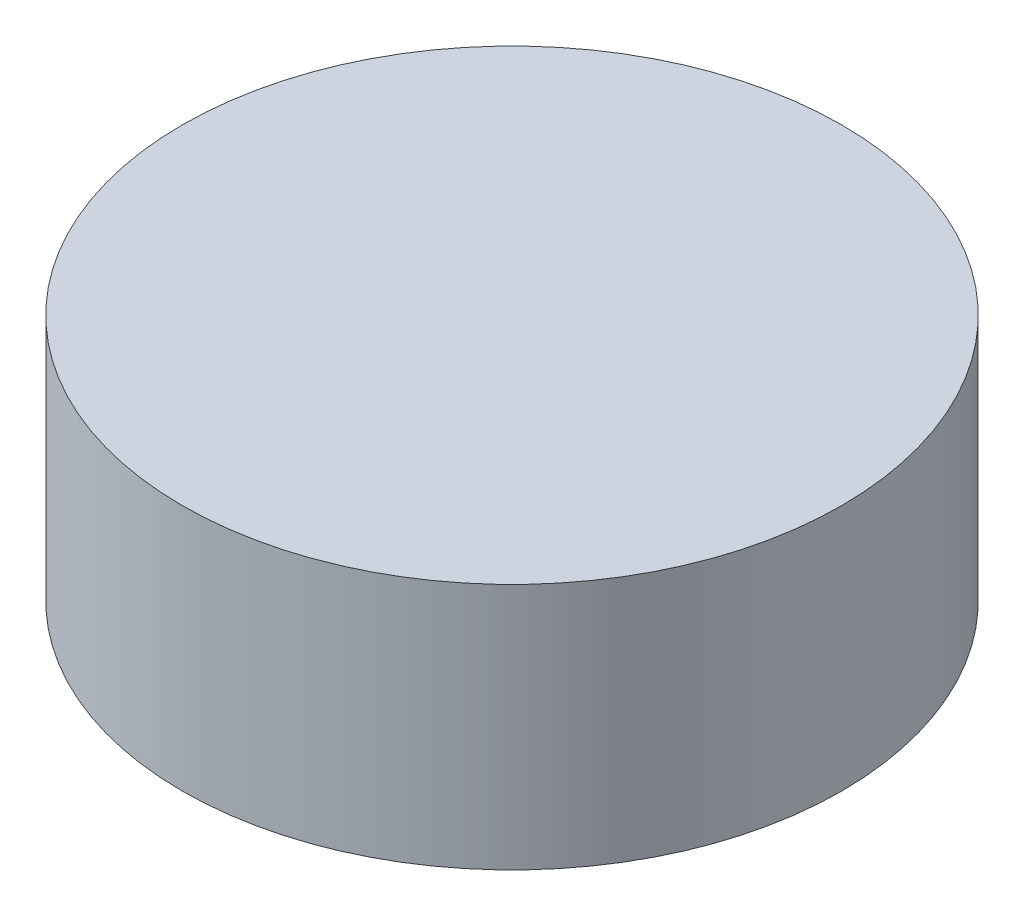
SolidWorks part; units mm, degrees
ref_plane "Front Plane" through (0, 0, 0) normal (0, 0, 1) x (1, 0, 0)
ref_plane "Top Plane" through (0, 0, 0) normal (0, 1, 0) x (1, 0, 0)
ref_plane "Right Plane" through (0, 0, 0) normal (1, 0, 0) x (0, 0, -1)
sketch "Sketch1" plane through (0, 0, 0) normal (0, 1, 0) x (1, 0, 0)
  circle A0 centre (0, 0) radius 0.4
extrude "Boss-Extrude1" add sketch "Sketch1" along normal blind 0.3
